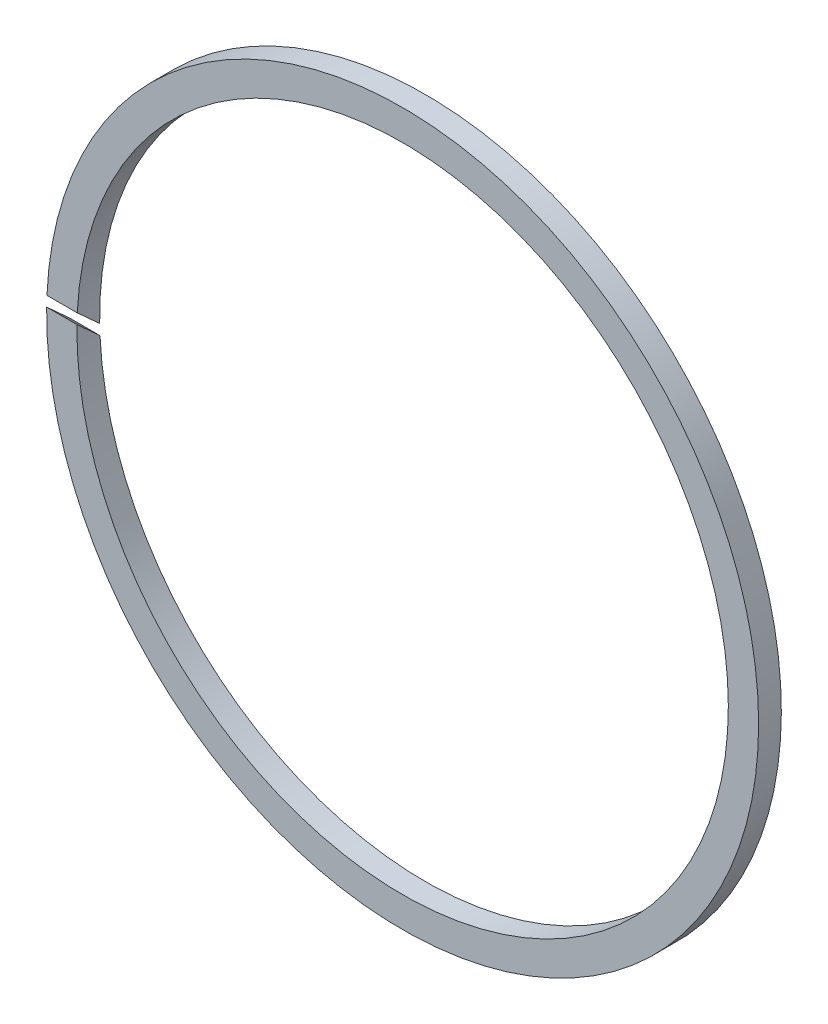
SolidWorks part; units mm, degrees
ref_plane "Front Plane" through (0, 0, 0) normal (0, 0, 1) x (1, 0, 0)
ref_plane "Top Plane" through (0, 0, 0) normal (0, 1, 0) x (1, 0, 0)
ref_plane "Right Plane" through (0, 0, 0) normal (1, 0, 0) x (0, 0, -1)
sketch "Sketch1" plane through (0, 0, 0) normal (0, 0, 1) x (1, 0, 0)
  circle A0 centre (0, 0) radius 47
  circle A1 centre (0, 0) radius 43
  dimension "D1" = 47
  dimension "D2" = 43
extrude "Boss-Extrude1" add sketch "Sketch1" along normal mid plane 3
sketch "Sketch2" plane through (0, 0, 0) normal (1, 0, 0) x (0, 0, -1)
  line L0 (0, 30.7314) -> (0, -40.9751) construction
  line L1 (-7.3864, 6.741) -> (7.3864, -6.741) construction
  line L2 (-7.7235, 6.3717) -> (7.0494, -7.1103)
  line L3 (-7.0494, 7.1103) -> (7.7235, -6.3717)
  line L4 (-7.0494, 7.1103) -> (-7.7235, 6.3717)
  line L5 (7.0494, -7.1103) -> (7.7235, -6.3717)
  dimension "D3" = 20
  dimension "D4" = 1
  dimension "D1" = 0.5
  dimension "D2" = 0.5
extrude "Cut-Extrude1" cut sketch "Sketch2" against normal through all
